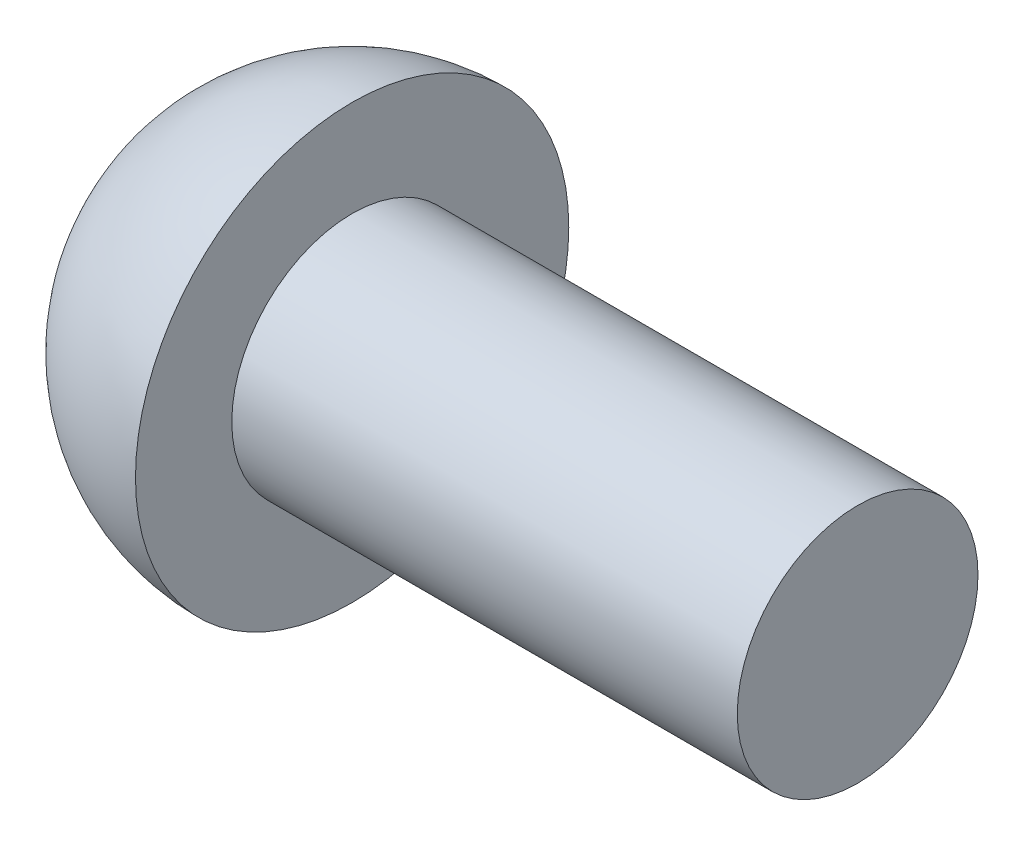
SolidWorks part; units mm, degrees
ref_plane "Front Plane" through (0, 0, 0) normal (0, 0, 1) x (1, 0, 0)
ref_plane "Top Plane" through (0, 0, 0) normal (0, 1, 0) x (1, 0, 0)
ref_plane "Right Plane" through (0, 0, 0) normal (1, 0, 0) x (0, 0, -1)
sketch "Sketch1" plane through (0, 0, 0) normal (0, 0, 1) x (1, 0, 0)
  line L0 (0, 0) -> (-30, 0)
  line L1 (-21, 9) -> (-21, 5)
  line L2 (-21, 5) -> (0, 5)
  line L3 (0, 5) -> (0, 0)
  arc A0 (-30, 0) -> (-21, 9) centre (-21, 0) cw
  point P5 (0, 0)
  point P8 (-23.3882, 0)
  point P9 (-26.3139, 0)
  point P10 (-28.6295, 0)
  point P11 (0, 0)
  point P12 (-28.0256, 0)
  point P13 (0, 0)
  dimension "D1" = 9
  dimension "D2" = 5
  dimension "D3" = 21
revolve "Revolve1" add sketch "Sketch1" angle 360 about L0
